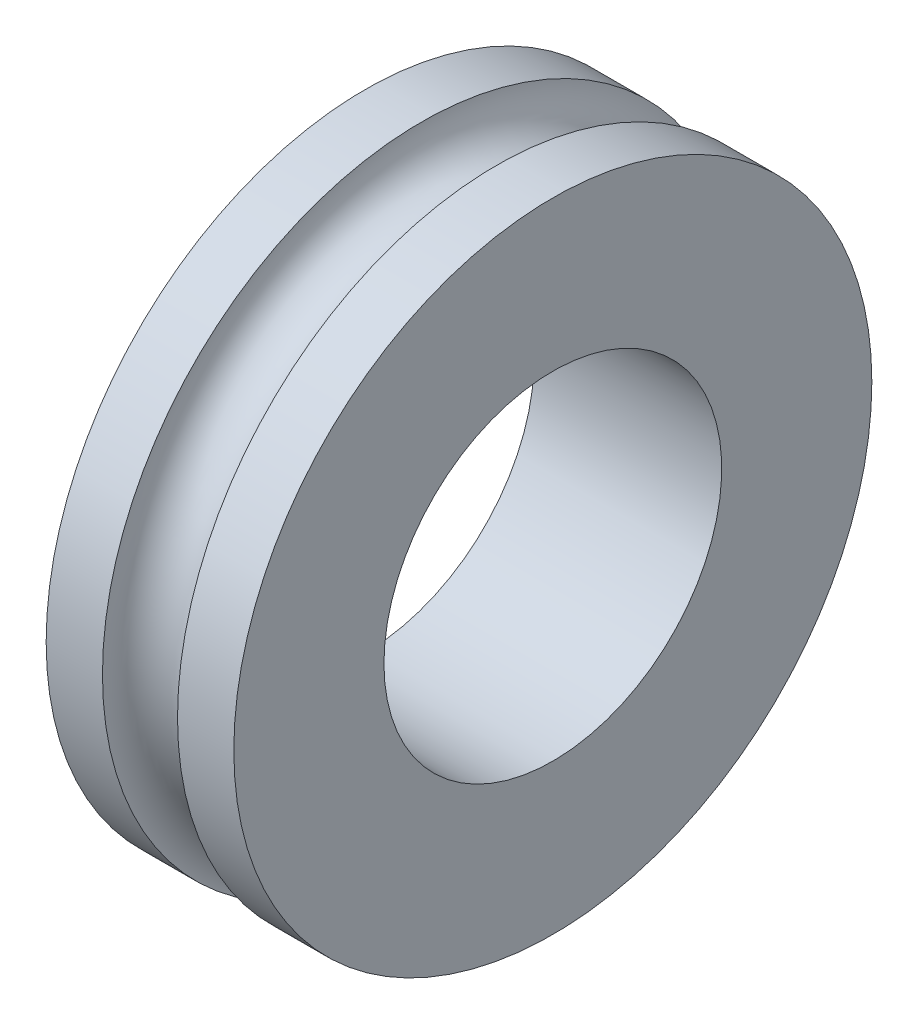
SolidWorks part; units mm, degrees
ref_plane "前视基准面" through (0, 0, 0) normal (0, 0, 1) x (1, 0, 0)
ref_plane "上视基准面" through (0, 0, 0) normal (0, 1, 0) x (1, 0, 0)
ref_plane "右视基准面" through (0, 0, 0) normal (1, 0, 0) x (0, 0, -1)
sketch "草图1" plane through (0, 0, 0) normal (0, 0, 1) x (1, 0, 0)
  line L0 (1, 8.5) -> (2.5, 8.5)
  line L1 (-2.5, 8.5) -> (-1, 8.5)
  line L2 (-2.5, 8.5) -> (-2.5, 4.5)
  line L3 (-2.5, 4.5) -> (2.5, 4.5)
  line L4 (2.5, 8.5) -> (2.5, 4.5)
  line L5 (-2.5, 8.5) -> (2.5, 4.5) construction
  line L6 (-2.5, 4.5) -> (2.5, 8.5) construction
  line L7 (0, 0) -> (8.9004, 0) construction
  arc A0 (-1, 8.5) -> (1, 8.5) centre (0, 8.5) ccw
  point P0 (0, 6.5)
  dimension "D4" = 2
  dimension "D1" = 4.5
  dimension "D2" = 8.5
  dimension "D3" = 5
revolve "旋转1" add sketch "草图1" angle 360 about L7
